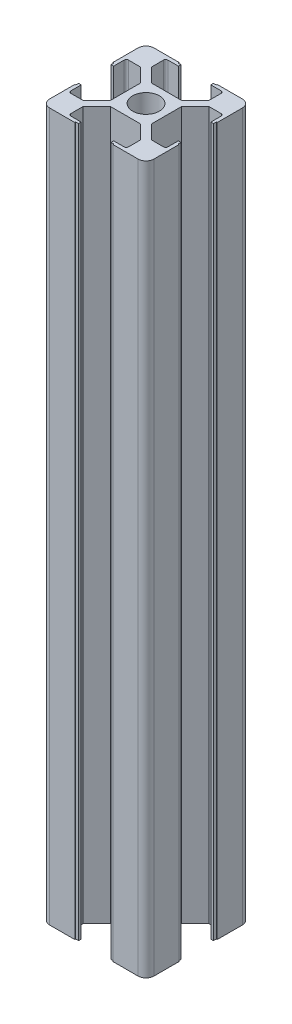
SolidWorks part; units mm, degrees
ref_plane "前视基准面" through (0, 0, 0) normal (0, 0, 1) x (1, 0, 0)
ref_plane "上视基准面" through (0, 0, 0) normal (0, 1, 0) x (1, 0, 0)
ref_plane "右视基准面" through (0, 0, 0) normal (1, 0, 0) x (0, 0, -1)
other "Configuration Table"
ref_plane "基准面1" through (0, 0, 9.9368) normal (0, 0, 1) x (1, 0, 0)
sketch "草图1" plane through (0, 0, 9.9368) normal (0, 0, 1) x (1, 0, 0)
  line L0 (-9.9368, 135) -> (-9.9368, 0)
  line L1 (-9.9368, 0) -> (9.9368, 0)
  line L2 (9.9368, 0) -> (9.9368, 135)
  line L3 (9.9368, 135) -> (-9.9368, 135)
  dimension "D1" = 135
extrude "凸台-拉伸1" add sketch "草图1" against normal blind 19.8735
sketch "草图2" plane through (0, 135, 0) normal (0, 1, 0) x (-1, 0, 0)
  line L0 (-3.65, -9.9368) -> (3.65, -9.9368)
  line L1 (3.65, -9.9368) -> (3.65, -9.76)
  line L2 (3.65, -9.76) -> (3.1, -9.76)
  line L3 (3.1, -9.76) -> (3.1, -9.26)
  line L4 (3.1, -9.26) -> (5.5, -9.26)
  line L5 (5.5, -9.26) -> (5.5, -6.56)
  line L6 (5.5, -6.56) -> (2.84, -3.9)
  line L7 (2.84, -3.9) -> (-2.84, -3.9)
  line L8 (-2.84, -3.9) -> (-5.5, -6.56)
  line L9 (-5.5, -6.56) -> (-5.5, -9.26)
  line L10 (-5.5, -9.26) -> (-3.1, -9.26)
  line L11 (-3.1, -9.26) -> (-3.1, -9.76)
  line L12 (-3.1, -9.76) -> (-3.65, -9.76)
  line L13 (-3.65, -9.76) -> (-3.65, -9.9368)
extrude "切除-拉伸1" cut sketch "草图2" against normal through all
sketch "草图3" plane through (0, 135, 0) normal (0, 1, 0) x (-1, 0, 0)
  line L0 (-9.9368, 3.65) -> (-9.9368, -3.65)
  line L1 (-9.9368, -3.65) -> (-9.76, -3.65)
  line L2 (-9.76, -3.65) -> (-9.76, -3.1)
  line L3 (-9.76, -3.1) -> (-9.26, -3.1)
  line L4 (-9.26, -3.1) -> (-9.26, -5.5)
  line L5 (-9.26, -5.5) -> (-6.56, -5.5)
  line L6 (-6.56, -5.5) -> (-3.9, -2.84)
  line L7 (-3.9, -2.84) -> (-3.9, 2.84)
  line L8 (-3.9, 2.84) -> (-6.56, 5.5)
  line L9 (-6.56, 5.5) -> (-9.26, 5.5)
  line L10 (-9.26, 5.5) -> (-9.26, 3.1)
  line L11 (-9.26, 3.1) -> (-9.76, 3.1)
  line L12 (-9.76, 3.1) -> (-9.76, 3.65)
  line L13 (-9.76, 3.65) -> (-9.9368, 3.65)
extrude "切除-拉伸2" cut sketch "草图3" against normal blind 135
sketch "草图4" plane through (0, 135, 0) normal (0, 1, 0) x (-1, 0, 0)
  line L0 (3.65, 9.9368) -> (-3.65, 9.9368)
  line L1 (-3.65, 9.9368) -> (-3.65, 9.76)
  line L2 (-3.65, 9.76) -> (-3.1, 9.76)
  line L3 (-3.1, 9.76) -> (-3.1, 9.26)
  line L4 (-3.1, 9.26) -> (-5.5, 9.26)
  line L5 (-5.5, 9.26) -> (-5.5, 6.56)
  line L6 (-5.5, 6.56) -> (-2.84, 3.9)
  line L7 (-2.84, 3.9) -> (2.84, 3.9)
  line L8 (2.84, 3.9) -> (5.5, 6.56)
  line L9 (5.5, 6.56) -> (5.5, 9.26)
  line L10 (5.5, 9.26) -> (3.1, 9.26)
  line L11 (3.1, 9.26) -> (3.1, 9.76)
  line L12 (3.1, 9.76) -> (3.65, 9.76)
  line L13 (3.65, 9.76) -> (3.65, 9.9368)
extrude "切除-拉伸3" cut sketch "草图4" against normal through all
sketch "草图5" plane through (0, 135, 0) normal (0, 1, 0) x (-1, 0, 0)
  line L0 (9.9368, -3.65) -> (9.9368, 3.65)
  line L1 (9.9368, 3.65) -> (9.76, 3.65)
  line L2 (9.76, 3.65) -> (9.76, 3.1)
  line L3 (9.76, 3.1) -> (9.26, 3.1)
  line L4 (9.26, 3.1) -> (9.26, 5.5)
  line L5 (9.26, 5.5) -> (6.56, 5.5)
  line L6 (6.56, 5.5) -> (3.9, 2.84)
  line L7 (3.9, 2.84) -> (3.9, -2.84)
  line L8 (3.9, -2.84) -> (6.56, -5.5)
  line L9 (6.56, -5.5) -> (9.26, -5.5)
  line L10 (9.26, -5.5) -> (9.26, -3.1)
  line L11 (9.26, -3.1) -> (9.76, -3.1)
  line L12 (9.76, -3.1) -> (9.76, -3.65)
  line L13 (9.76, -3.65) -> (9.9368, -3.65)
extrude "切除-拉伸4" cut sketch "草图5" against normal through all
hole_wizard "Ø5.0 (5) 直径孔1" positions "草图7" profile "草图6" hole size "Ø5.0" standard "ANSI Metric"
sketch "草图7" plane through (3.9, 0, 0) normal (1, 0, 0) x (0, 0, -1)
  point P0 (0, 123)
  point P1 (0, 0)
sketch "草图6" plane through (3.9, 123, 0) normal (0, 1, 0) x (0, 0, -1)
  line L0 (0, 0) -> (0, 7.8)
  line L1 (0, 7.8) -> (2.5, 7.8)
  line L2 (2.5, 7.8) -> (2.5, 0)
  line L5 (2.5, 0) -> (0, 0)
  line L10 (0, 7.8) -> (-2.5, 7.8) construction
  line L11 (0, -6.35) -> (0, 107.95) construction
  dimension "孔直径" = 5
  dimension "孔深度" = 7.8
  dimension "导头角度" = 180
hole_wizard "Ø5.0 (5) 直径孔2" positions "草图9" profile "草图8" hole size "Ø5.0" standard "ANSI Metric"
sketch "草图9" plane through (0, 0, -3.9) normal (0, 0, -1) x (-1, 0, 0)
  point P0 (0, 12)
sketch "草图8" plane through (0, 12, -3.9) normal (1, 0, 0) x (0, 1, 0)
  line L0 (0, 0) -> (0, 7.8)
  line L1 (0, 7.8) -> (2.5, 7.8)
  line L2 (2.5, 7.8) -> (2.5, 0)
  line L5 (2.5, 0) -> (0, 0)
  line L10 (0, 7.8) -> (-2.5, 7.8) construction
  line L11 (0, -6.35) -> (0, 107.95) construction
  dimension "孔直径" = 5
  dimension "孔深度" = 7.8
  dimension "导头角度" = 180
hole_wizard "Ø5.0 (5) 直径孔3" positions "草图11" profile "草图10" hole size "Ø5.0" standard "ANSI Metric"
sketch "草图11" plane through (-3.9, 0, 0) normal (-1, 0, 0) x (0, 0, 1)
  point P0 (0, 12)
sketch "草图10" plane through (-3.9, 12, 0) normal (0, 1, 0) x (0, 0, 1)
  line L0 (0, 0) -> (0, 11.7)
  line L1 (0, 11.7) -> (2.5, 11.7)
  line L2 (2.5, 11.7) -> (2.5, 0)
  line L5 (2.5, 0) -> (0, 0)
  line L10 (0, 11.7) -> (-2.5, 11.7) construction
  line L11 (0, -6.35) -> (0, 107.95) construction
  dimension "孔直径" = 5
  dimension "孔深度" = 11.7
  dimension "导头角度" = 180
hole_wizard "Ø5.0 (5) 直径孔4" positions "草图13" profile "草图12" hole size "Ø5.0" standard "ANSI Metric"
sketch "草图13" plane through (0, 0, 3.9) normal (0, 0, 1) x (1, 0, 0)
  point P0 (0, 123)
sketch "草图12" plane through (0, 123, 3.9) normal (1, 0, 0) x (0, -1, 0)
  line L0 (0, 0) -> (0, 11.7)
  line L1 (0, 11.7) -> (2.5, 11.7)
  line L2 (2.5, 11.7) -> (2.5, 0)
  line L5 (2.5, 0) -> (0, 0)
  line L10 (0, 11.7) -> (-2.5, 11.7) construction
  line L11 (0, -6.35) -> (0, 107.95) construction
  dimension "孔直径" = 5
  dimension "孔深度" = 11.7
  dimension "导头角度" = 180
hole_wizard "Ø5.1 (5.1) 直径孔1" positions "草图15" profile "草图14" hole size "Ø5.1" standard "ANSI Metric"
sketch "草图15" plane through (0, 0, 0) normal (0, -1, 0) x (-1, 0, 0)
  point P0 (0, 0)
sketch "草图14" plane through (0, 0, 0) normal (1, 0, 0) x (0, 0, -1)
  line L0 (0, 0) -> (0, 363.8049)
  line L1 (0, 363.8049) -> (2.55, 363.8049)
  line L2 (2.55, 363.8049) -> (2.55, 0)
  line L5 (2.55, 0) -> (0, 0)
  line L10 (0, 363.8049) -> (-2.55, 363.8049) construction
  line L11 (0, -6.35) -> (0, 107.95) construction
  dimension "孔直径" = 5.1
  dimension "孔深度" = 363.8049
  dimension "导头角度" = 180
fillet "圆角1" radius 0.4 8 edges at (9.26, 67.5, 5.5) (5.5, 67.5, -9.26) (-5.5, 67.5, -9.26) (9.26, 67.5, -5.5) (-9.26, 67.5, 5.5) (-9.26, 67.5, -5.5) (-5.5, 67.5, 9.26) (5.5, 67.5, 9.26)
fillet "圆角2" radius 1.5 4 edges at (-9.9368, 67.5, -9.9368) (9.9368, 67.5, -9.9368) (-9.9368, 67.5, 9.9368) (9.9368, 67.5, 9.9368)
